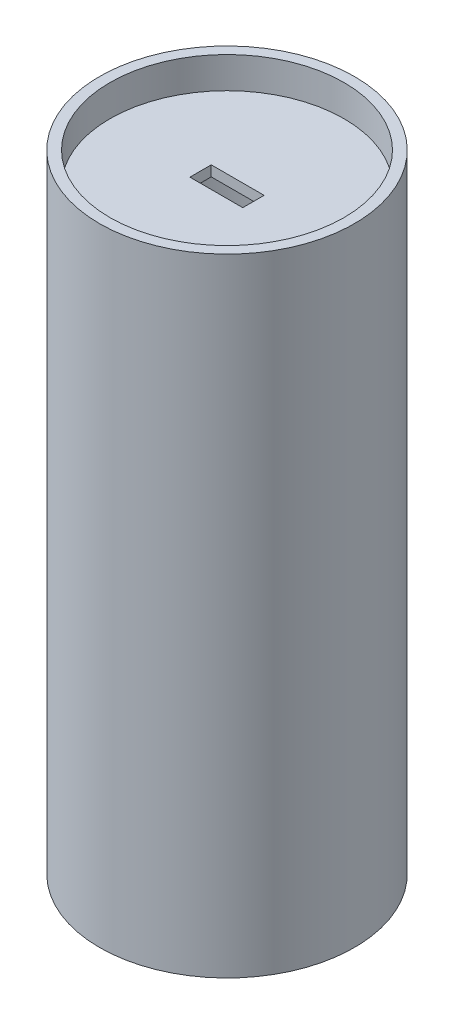
SolidWorks part; units mm, degrees
ref_plane "Front Plane" through (0, 0, 0) normal (0, 0, 1) x (1, 0, 0)
ref_plane "Top Plane" through (0, 0, 0) normal (0, 1, 0) x (1, 0, 0)
ref_plane "Right Plane" through (0, 0, 0) normal (1, 0, 0) x (0, 0, -1)
sketch "Sketch1" plane through (0, 0, 0) normal (0, 1, 0) x (1, 0, 0)
  circle A0 centre (0, 0) radius 61
  circle A1 centre (0, 0) radius 56
extrude "Boss-Extrude1" add sketch "Sketch1" along normal blind 300 contours A0 A1
ref_plane "Plane1" through (0, 20, 0) normal (0, 1, 0) x (1, 0, 0)
sketch "Sketch3" plane through (0, 20, 0) normal (0, 1, 0) x (1, 0, 0)
  circle A0 centre (0, 0) radius 56
extrude "Boss-Extrude2" add sketch "Sketch3" along normal blind 5
sketch "Sketch4" plane through (0, 20, 0) normal (0, -1, 0) x (1, 0, 0)
  circle A0 centre (-3, 0) radius 1.5
  circle A3 centre (3, 0) radius 1.5
  dimension "D1" = 3
  dimension "D2" = 3
  dimension "D3" = 6
extrude "Cut-Extrude1" cut sketch "Sketch4" against normal up to next
ref_plane "Plane2" through (0, 280, 0) normal (0, 1, 0) x (1, 0, 0)
sketch "Sketch5" plane through (0, 280, 0) normal (0, 1, 0) x (1, 0, 0)
  circle A0 centre (0, 0) radius 56
extrude "Boss-Extrude3" add sketch "Sketch5" along normal blind 5
sketch "Sketch6" plane through (0, 285, 0) normal (0, 1, 0) x (1, 0, 0)
  line L1 (-12.6506, 5.1122) -> (12.6506, 5.1122)
  line L2 (-12.6506, 5.1122) -> (-12.6506, -5.1122)
  line L3 (-12.6506, -5.1122) -> (12.6506, -5.1122)
  line L4 (12.6506, 5.1122) -> (12.6506, -5.1122)
  line L5 (-12.6506, 5.1122) -> (12.6506, -5.1122) construction
  line L6 (-12.6506, -5.1122) -> (12.6506, 5.1122) construction
  point P0 (0, 0)
extrude "Cut-Extrude2" cut sketch "Sketch6" against normal up to next
